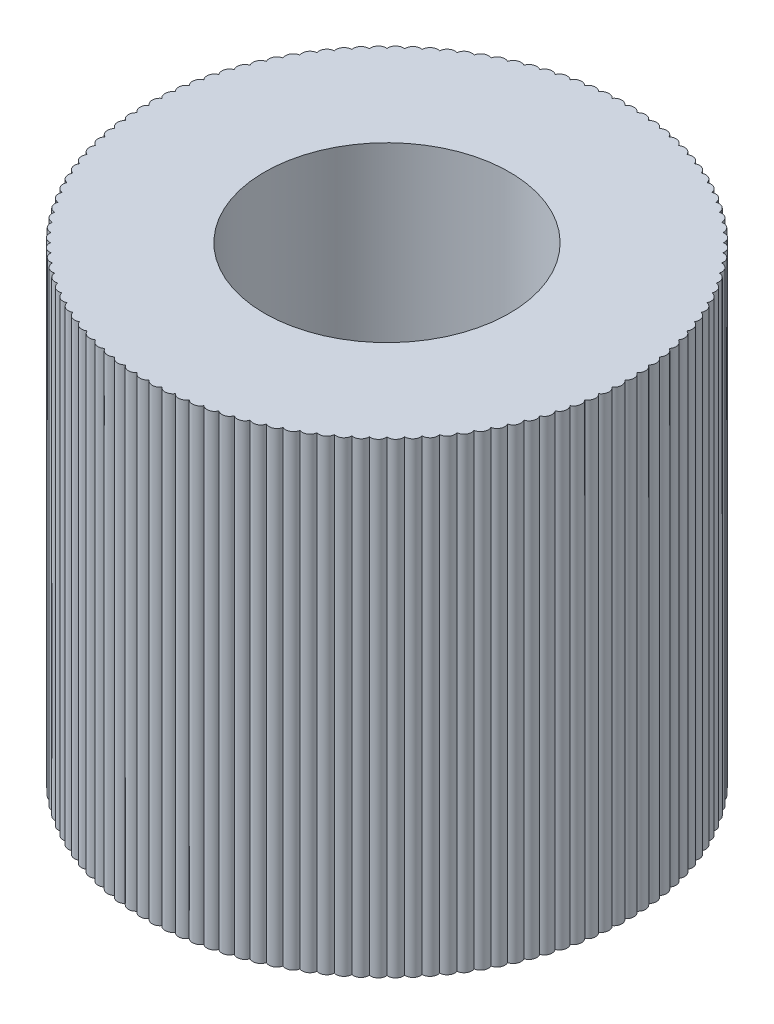
SolidWorks part; units mm, degrees
ref_plane "Front Plane" through (0, 0, 0) normal (0, 0, 1) x (1, 0, 0)
ref_plane "Top Plane" through (0, 0, 0) normal (0, 1, 0) x (1, 0, 0)
ref_plane "Right Plane" through (0, 0, 0) normal (1, 0, 0) x (0, 0, -1)
sketch "Sketch1" plane through (0, 0, 0) normal (0, 1, 0) x (1, 0, 0)
  line L0 (0, 0) -> (-0.1374, 2.6214) construction
  line L1 (0, 0) -> (0, 5.1) construction
  line L2 (-0.2669, 5.093) -> (0, 5.1) construction
  line L3 (-0.2669, 5.093) -> (-0.1309, 4.9983) construction
  line L4 (-0.1309, 4.9983) -> (0, 5.1) construction
  line L5 (-0.2617, 4.9931) -> (-0.2669, 5.093) construction
  line L6 (-0.4168, 4.9908) -> (0.0711, 5.0036) construction
  circle A0 centre (0, 0) radius 2.625
  circle A1 centre (0, 0) radius 5 construction
  arc A3 (0, 5.1) -> (-0.2669, 5.093) centre (-0.1309, 4.9983) ccw
  arc A4 (0.2669, 5.093) -> (0, 5.1) centre (0.1309, 4.9983) ccw
  arc A5 (0.5331, 5.0721) -> (0.2669, 5.093) centre (0.3923, 4.9846) ccw
  arc A6 (0.7978, 5.0372) -> (0.5331, 5.0721) centre (0.6526, 4.9572) ccw
  arc A7 (1.0603, 4.9886) -> (0.7978, 5.0372) centre (0.9112, 4.9163) ccw
  arc A8 (1.32, 4.9262) -> (1.0603, 4.9886) centre (1.1672, 4.8618) ccw
  arc A9 (1.576, 4.8504) -> (1.32, 4.9262) centre (1.4201, 4.7941) ccw
  arc A10 (1.8277, 4.7613) -> (1.576, 4.8504) centre (1.669, 4.7132) ccw
  arc A11 (2.0744, 4.6591) -> (1.8277, 4.7613) centre (1.9134, 4.6194) ccw
  arc A12 (2.3154, 4.5441) -> (2.0744, 4.6591) centre (2.1526, 4.5129) ccw
  arc A13 (2.55, 4.4167) -> (2.3154, 4.5441) centre (2.3858, 4.3941) ccw
  arc A14 (2.7777, 4.2772) -> (2.55, 4.4167) centre (2.6125, 4.2632) ccw
  arc A15 (2.9977, 4.126) -> (2.7777, 4.2772) centre (2.832, 4.1206) ccw
  arc A16 (3.2095, 3.9634) -> (2.9977, 4.126) centre (3.0438, 3.9668) ccw
  arc A17 (3.4126, 3.79) -> (3.2095, 3.9634) centre (3.2472, 3.802) ccw
  arc A18 (3.6062, 3.6062) -> (3.4126, 3.79) centre (3.4418, 3.6269) ccw
  arc A19 (3.79, 3.4126) -> (3.6062, 3.6062) centre (3.6269, 3.4418) ccw
  arc A20 (3.9634, 3.2095) -> (3.79, 3.4126) centre (3.802, 3.2472) ccw
  arc A21 (4.126, 2.9977) -> (3.9634, 3.2095) centre (3.9668, 3.0438) ccw
  arc A22 (4.2772, 2.7777) -> (4.126, 2.9977) centre (4.1206, 2.832) ccw
  arc A23 (4.4167, 2.55) -> (4.2772, 2.7777) centre (4.2632, 2.6125) ccw
  arc A24 (4.5441, 2.3154) -> (4.4167, 2.55) centre (4.3941, 2.3858) ccw
  arc A25 (4.6591, 2.0744) -> (4.5441, 2.3154) centre (4.5129, 2.1526) ccw
  arc A26 (4.7613, 1.8277) -> (4.6591, 2.0744) centre (4.6194, 1.9134) ccw
  arc A27 (4.8504, 1.576) -> (4.7613, 1.8277) centre (4.7132, 1.669) ccw
  arc A28 (4.9262, 1.32) -> (4.8504, 1.576) centre (4.7941, 1.4201) ccw
  arc A29 (4.9886, 1.0603) -> (4.9262, 1.32) centre (4.8618, 1.1672) ccw
  arc A30 (5.0372, 0.7978) -> (4.9886, 1.0603) centre (4.9163, 0.9112) ccw
  arc A31 (5.0721, 0.5331) -> (5.0372, 0.7978) centre (4.9572, 0.6526) ccw
  arc A32 (5.093, 0.2669) -> (5.0721, 0.5331) centre (4.9846, 0.3923) ccw
  arc A33 (5.1, 0) -> (5.093, 0.2669) centre (4.9983, 0.1309) ccw
  arc A34 (5.093, -0.2669) -> (5.1, 0) centre (4.9983, -0.1309) ccw
  arc A35 (5.0721, -0.5331) -> (5.093, -0.2669) centre (4.9846, -0.3923) ccw
  arc A36 (5.0372, -0.7978) -> (5.0721, -0.5331) centre (4.9572, -0.6526) ccw
  arc A37 (4.9886, -1.0603) -> (5.0372, -0.7978) centre (4.9163, -0.9112) ccw
  arc A38 (4.9262, -1.32) -> (4.9886, -1.0603) centre (4.8618, -1.1672) ccw
  arc A39 (4.8504, -1.576) -> (4.9262, -1.32) centre (4.7941, -1.4201) ccw
  arc A40 (4.7613, -1.8277) -> (4.8504, -1.576) centre (4.7132, -1.669) ccw
  arc A41 (4.6591, -2.0744) -> (4.7613, -1.8277) centre (4.6194, -1.9134) ccw
  arc A42 (4.5441, -2.3154) -> (4.6591, -2.0744) centre (4.5129, -2.1526) ccw
  arc A43 (4.4167, -2.55) -> (4.5441, -2.3154) centre (4.3941, -2.3858) ccw
  arc A44 (4.2772, -2.7777) -> (4.4167, -2.55) centre (4.2632, -2.6125) ccw
  arc A45 (4.126, -2.9977) -> (4.2772, -2.7777) centre (4.1206, -2.832) ccw
  arc A46 (3.9634, -3.2095) -> (4.126, -2.9977) centre (3.9668, -3.0438) ccw
  arc A47 (3.79, -3.4126) -> (3.9634, -3.2095) centre (3.802, -3.2472) ccw
  arc A48 (3.6062, -3.6062) -> (3.79, -3.4126) centre (3.6269, -3.4418) ccw
  arc A49 (3.4126, -3.79) -> (3.6062, -3.6062) centre (3.4418, -3.6269) ccw
  arc A50 (3.2095, -3.9634) -> (3.4126, -3.79) centre (3.2472, -3.802) ccw
  arc A51 (2.9977, -4.126) -> (3.2095, -3.9634) centre (3.0438, -3.9668) ccw
  arc A52 (2.7777, -4.2772) -> (2.9977, -4.126) centre (2.832, -4.1206) ccw
  arc A53 (2.55, -4.4167) -> (2.7777, -4.2772) centre (2.6125, -4.2632) ccw
  arc A54 (2.3154, -4.5441) -> (2.55, -4.4167) centre (2.3858, -4.3941) ccw
  arc A55 (2.0744, -4.6591) -> (2.3154, -4.5441) centre (2.1526, -4.5129) ccw
  arc A56 (1.8277, -4.7613) -> (2.0744, -4.6591) centre (1.9134, -4.6194) ccw
  arc A57 (1.576, -4.8504) -> (1.8277, -4.7613) centre (1.669, -4.7132) ccw
  arc A58 (1.32, -4.9262) -> (1.576, -4.8504) centre (1.4201, -4.7941) ccw
  arc A59 (1.0603, -4.9886) -> (1.32, -4.9262) centre (1.1672, -4.8618) ccw
  arc A60 (0.7978, -5.0372) -> (1.0603, -4.9886) centre (0.9112, -4.9163) ccw
  arc A61 (0.5331, -5.0721) -> (0.7978, -5.0372) centre (0.6526, -4.9572) ccw
  arc A62 (0.2669, -5.093) -> (0.5331, -5.0721) centre (0.3923, -4.9846) ccw
  arc A63 (0, -5.1) -> (0.2669, -5.093) centre (0.1309, -4.9983) ccw
  arc A64 (-0.2669, -5.093) -> (0, -5.1) centre (-0.1309, -4.9983) ccw
  arc A65 (-0.5331, -5.0721) -> (-0.2669, -5.093) centre (-0.3923, -4.9846) ccw
  arc A66 (-0.7978, -5.0372) -> (-0.5331, -5.0721) centre (-0.6526, -4.9572) ccw
  arc A67 (-1.0603, -4.9886) -> (-0.7978, -5.0372) centre (-0.9112, -4.9163) ccw
  arc A68 (-1.32, -4.9262) -> (-1.0603, -4.9886) centre (-1.1672, -4.8618) ccw
  arc A69 (-1.576, -4.8504) -> (-1.32, -4.9262) centre (-1.4201, -4.7941) ccw
  arc A70 (-1.8277, -4.7613) -> (-1.576, -4.8504) centre (-1.669, -4.7132) ccw
  arc A71 (-2.0744, -4.6591) -> (-1.8277, -4.7613) centre (-1.9134, -4.6194) ccw
  arc A72 (-2.3154, -4.5441) -> (-2.0744, -4.6591) centre (-2.1526, -4.5129) ccw
  arc A73 (-2.55, -4.4167) -> (-2.3154, -4.5441) centre (-2.3858, -4.3941) ccw
  arc A74 (-2.7777, -4.2772) -> (-2.55, -4.4167) centre (-2.6125, -4.2632) ccw
  arc A75 (-2.9977, -4.126) -> (-2.7777, -4.2772) centre (-2.832, -4.1206) ccw
  arc A76 (-3.2095, -3.9634) -> (-2.9977, -4.126) centre (-3.0438, -3.9668) ccw
  arc A77 (-3.4126, -3.79) -> (-3.2095, -3.9634) centre (-3.2472, -3.802) ccw
  arc A78 (-3.6062, -3.6062) -> (-3.4126, -3.79) centre (-3.4418, -3.6269) ccw
  arc A79 (-3.79, -3.4126) -> (-3.6062, -3.6062) centre (-3.6269, -3.4418) ccw
  arc A80 (-3.9634, -3.2095) -> (-3.79, -3.4126) centre (-3.802, -3.2472) ccw
  arc A81 (-4.126, -2.9977) -> (-3.9634, -3.2095) centre (-3.9668, -3.0438) ccw
  arc A82 (-4.2772, -2.7777) -> (-4.126, -2.9977) centre (-4.1206, -2.832) ccw
  arc A83 (-4.4167, -2.55) -> (-4.2772, -2.7777) centre (-4.2632, -2.6125) ccw
  arc A84 (-4.5441, -2.3154) -> (-4.4167, -2.55) centre (-4.3941, -2.3858) ccw
  arc A85 (-4.6591, -2.0744) -> (-4.5441, -2.3154) centre (-4.5129, -2.1526) ccw
  arc A86 (-4.7613, -1.8277) -> (-4.6591, -2.0744) centre (-4.6194, -1.9134) ccw
  arc A87 (-4.8504, -1.576) -> (-4.7613, -1.8277) centre (-4.7132, -1.669) ccw
  arc A88 (-4.9262, -1.32) -> (-4.8504, -1.576) centre (-4.7941, -1.4201) ccw
  arc A89 (-4.9886, -1.0603) -> (-4.9262, -1.32) centre (-4.8618, -1.1672) ccw
  arc A90 (-5.0372, -0.7978) -> (-4.9886, -1.0603) centre (-4.9163, -0.9112) ccw
  arc A91 (-5.0721, -0.5331) -> (-5.0372, -0.7978) centre (-4.9572, -0.6526) ccw
  arc A92 (-5.093, -0.2669) -> (-5.0721, -0.5331) centre (-4.9846, -0.3923) ccw
  arc A93 (-5.1, 0) -> (-5.093, -0.2669) centre (-4.9983, -0.1309) ccw
  arc A94 (-5.093, 0.2669) -> (-5.1, 0) centre (-4.9983, 0.1309) ccw
  arc A95 (-5.0721, 0.5331) -> (-5.093, 0.2669) centre (-4.9846, 0.3923) ccw
  arc A96 (-5.0372, 0.7978) -> (-5.0721, 0.5331) centre (-4.9572, 0.6526) ccw
  arc A97 (-4.9886, 1.0603) -> (-5.0372, 0.7978) centre (-4.9163, 0.9112) ccw
  arc A98 (-4.9262, 1.32) -> (-4.9886, 1.0603) centre (-4.8618, 1.1672) ccw
  arc A99 (-4.8504, 1.576) -> (-4.9262, 1.32) centre (-4.7941, 1.4201) ccw
  arc A100 (-4.7613, 1.8277) -> (-4.8504, 1.576) centre (-4.7132, 1.669) ccw
  arc A101 (-4.6591, 2.0744) -> (-4.7613, 1.8277) centre (-4.6194, 1.9134) ccw
  arc A102 (-4.5441, 2.3154) -> (-4.6591, 2.0744) centre (-4.5129, 2.1526) ccw
  arc A103 (-4.4167, 2.55) -> (-4.5441, 2.3154) centre (-4.3941, 2.3858) ccw
  arc A104 (-4.2772, 2.7777) -> (-4.4167, 2.55) centre (-4.2632, 2.6125) ccw
  arc A105 (-4.126, 2.9977) -> (-4.2772, 2.7777) centre (-4.1206, 2.832) ccw
  arc A106 (-3.9634, 3.2095) -> (-4.126, 2.9977) centre (-3.9668, 3.0438) ccw
  arc A107 (-3.79, 3.4126) -> (-3.9634, 3.2095) centre (-3.802, 3.2472) ccw
  arc A108 (-3.6062, 3.6062) -> (-3.79, 3.4126) centre (-3.6269, 3.4418) ccw
  arc A109 (-3.4126, 3.79) -> (-3.6062, 3.6062) centre (-3.4418, 3.6269) ccw
  arc A110 (-3.2095, 3.9634) -> (-3.4126, 3.79) centre (-3.2472, 3.802) ccw
  arc A111 (-2.9977, 4.126) -> (-3.2095, 3.9634) centre (-3.0438, 3.9668) ccw
  arc A112 (-2.7777, 4.2772) -> (-2.9977, 4.126) centre (-2.832, 4.1206) ccw
  arc A113 (-2.55, 4.4167) -> (-2.7777, 4.2772) centre (-2.6125, 4.2632) ccw
  arc A114 (-2.3154, 4.5441) -> (-2.55, 4.4167) centre (-2.3858, 4.3941) ccw
  arc A115 (-2.0744, 4.6591) -> (-2.3154, 4.5441) centre (-2.1526, 4.5129) ccw
  arc A116 (-1.8277, 4.7613) -> (-2.0744, 4.6591) centre (-1.9134, 4.6194) ccw
  arc A117 (-1.576, 4.8504) -> (-1.8277, 4.7613) centre (-1.669, 4.7132) ccw
  arc A118 (-1.32, 4.9262) -> (-1.576, 4.8504) centre (-1.4201, 4.7941) ccw
  arc A119 (-1.0603, 4.9886) -> (-1.32, 4.9262) centre (-1.1672, 4.8618) ccw
  arc A120 (-0.7978, 5.0372) -> (-1.0603, 4.9886) centre (-0.9112, 4.9163) ccw
  arc A121 (-0.5331, 5.0721) -> (-0.7978, 5.0372) centre (-0.6526, 4.9572) ccw
  arc A122 (-0.2669, 5.093) -> (-0.5331, 5.0721) centre (-0.3923, 4.9846) ccw
  point P370 (0, 0)
  dimension "D1" = 5.25
  dimension "D2" = 10
  dimension "D3" = 3
  dimension "D4" = 5.1
  dimension "D5" = 120
extrude "Boss-Extrude1" add sketch "Sketch1" along normal blind 10 contours A3 A122 A121 A120 A119 A118 A117 A116 A115 A114 A113 A112 A111 A110 A109 A108 A107 A106 A105 A104 A103 A102 A101 A100 A99 A98 A97 A96 A95 A94 A93 A92 A91 A90 A89 A88 A87 A86 A85 A84 A83 A82 A81 A80 A79 A78 A77 A76 A75 A74 A73
